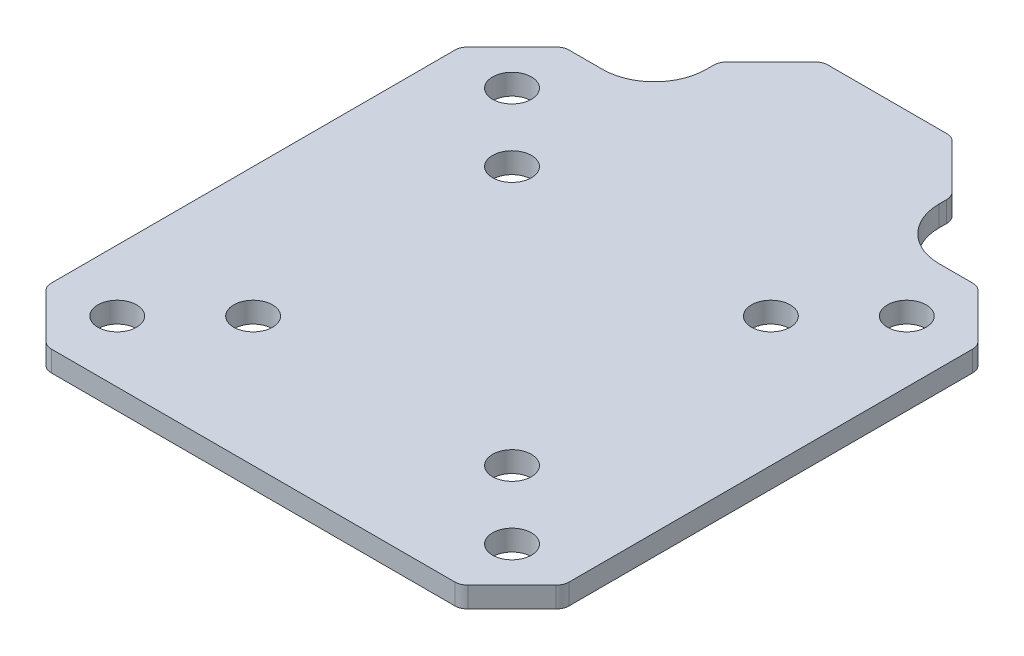
SolidWorks part; units mm, degrees
ref_plane "Front Plane" through (0, 0, 0) normal (0, 0, 1) x (1, 0, 0)
ref_plane "Top Plane" through (0, 0, 0) normal (0, 1, 0) x (1, 0, 0)
ref_plane "Right Plane" through (0, 0, 0) normal (1, 0, 0) x (0, 0, -1)
sketch "Sketch1" plane through (0, 0, 0) normal (0, 1, 0) x (1, 0, 0)
  line L0 (13, 20) -> (20, 20)
  line L1 (-20, -20) -> (20, -20)
  line L2 (-20, -20) -> (-20, 20)
  line L3 (-20, 20) -> (-13, 20)
  line L4 (20, -20) -> (20, 20)
  line L6 (-9, 24) -> (-9, 29)
  line L7 (-15.25, -15.25) -> (15.25, -15.25) construction
  line L8 (-15.25, -15.25) -> (-15.25, 15.25) construction
  line L9 (-15.25, 15.25) -> (15.25, 15.25) construction
  line L10 (15.25, -15.25) -> (15.25, 15.25) construction
  line L11 (-9, 29) -> (9, 29)
  line L12 (9, 24) -> (9, 29)
  line L13 (-10, -10) -> (10, -10) construction
  line L14 (-10, -10) -> (-10, 10) construction
  line L15 (-10, 10) -> (10, 10) construction
  line L16 (10, -10) -> (10, 10) construction
  circle A0 centre (-15.25, 15.25) radius 1.5
  circle A1 centre (-10, 10) radius 1.5
  circle A2 centre (10, 10) radius 1.5
  circle A3 centre (-10, -10) radius 1.5
  circle A4 centre (-15.25, -15.25) radius 1.5
  circle A5 centre (15.25, -15.25) radius 1.5
  circle A6 centre (10, -10) radius 1.5
  circle A7 centre (15.25, 15.25) radius 1.5
  arc A8 (13, 20) -> (9, 24) centre (13, 24) cw
  arc A9 (-13, 20) -> (-9, 24) centre (-13, 24) ccw
  point P0 (0, 0)
  point P6 (0, 0)
  point P11 (0, 0)
  point P24 (0, 29)
  point P25 (0, -20)
  point P28 (9, 20)
  point P29 (0, 15.25)
  point P30 (0, 10)
  point P31 (-20, 0)
  point P32 (-15.25, 0)
  point P33 (-10, 0)
  dimension "D3" = 3
  dimension "D8" = 4
  dimension "D1" = 40
  dimension "D2" = 40
  dimension "D4" = 30.5
  dimension "D5" = 20
  dimension "D6" = 18
  dimension "D7" = 9
extrude "Boss-Extrude1" add sketch "Sketch1" along normal blind 1.6
chamfer "Chamfer1" distance 4 angle 45 6 edges at (9, 0.8, -29) (-9, 0.8, -29) (-20, 0.8, -20) (20, 0.8, -20) (20, 0.8, 20) (-20, 0.8, 20)
fillet "Fillet1" radius 1 12 edges at (-5, 0.8, -29) (-9, 0.8, -25) (-16, 0.8, -20) (-20, 0.8, -16) (5, 0.8, -29) (9, 0.8, -25) (16, 0.8, -20) (20, 0.8, -16) (20, 0.8, 16) (16, 0.8, 20) (-16, 0.8, 20) (-20, 0.8, 16)
